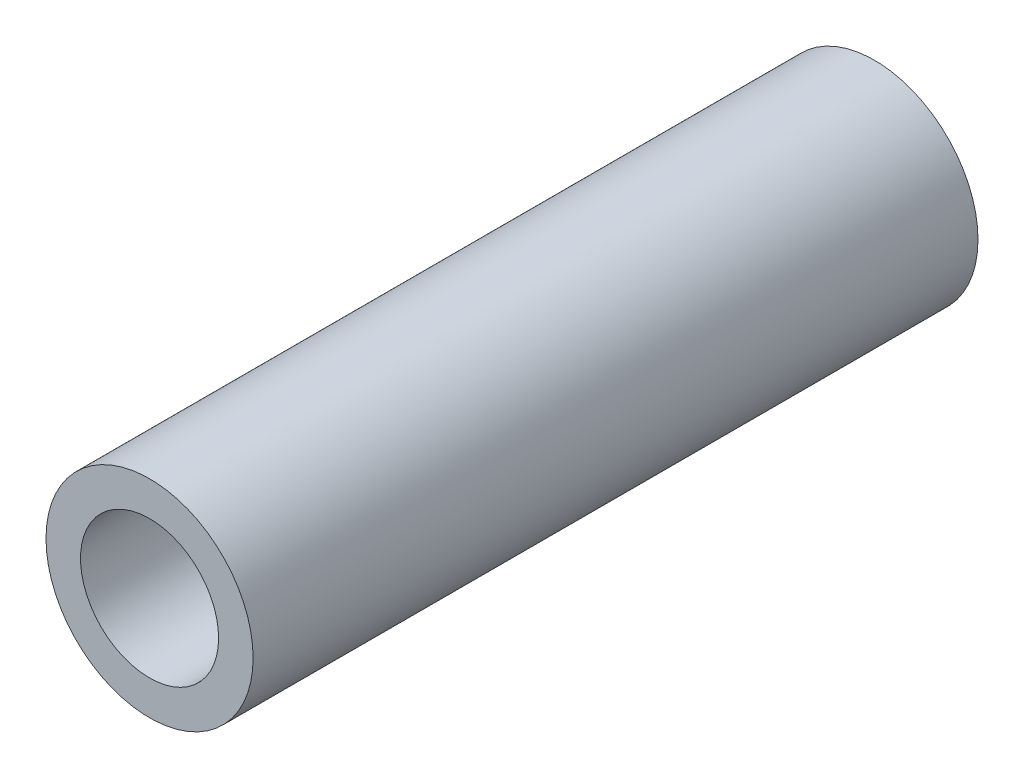
SolidWorks part; units mm, degrees
ref_plane "Płaszczyzna przednia" through (0, 0, 0) normal (0, 0, 1) x (1, 0, 0)
ref_plane "Płaszczyzna górna" through (0, 0, 0) normal (0, 1, 0) x (1, 0, 0)
ref_plane "Płaszczyzna prawa" through (0, 0, 0) normal (1, 0, 0) x (0, 0, -1)
sketch "Szkic1" plane through (0, 0, 0) normal (0, 0, 1) x (1, 0, 0)
  circle A0 centre (0, 0) radius 6
  circle A1 centre (0, 0) radius 9
  dimension "D1" = 12
  dimension "D2" = 18
extrude "Dodanie-wyciągnięcie1" add sketch "Szkic1" along normal blind 63 contours A1 A0
